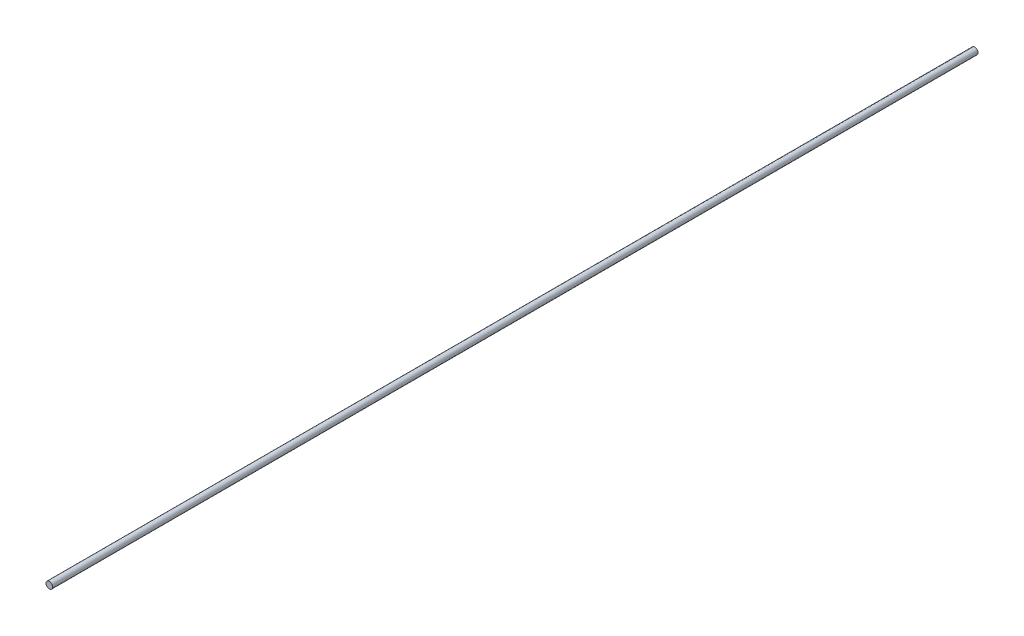
SolidWorks part; units mm, degrees
material "ASTM A36 Steel"
ref_plane "Front Plane" through (0, 0, 0) normal (0, 0, 1) x (1, 0, 0)
ref_plane "Top Plane" through (0, 0, 0) normal (0, 1, 0) x (1, 0, 0)
ref_plane "Right Plane" through (0, 0, 0) normal (1, 0, 0) x (0, 0, -1)
sketch "Sketch1" plane through (0, 0, 0) normal (0, 0, 1) x (1, 0, 0)
  circle A0 centre (-13.1321, 3.4528) radius 6
  dimension "D1" = 12
extrude "Boss-Extrude1" add sketch "Sketch1" along normal blind 1700
